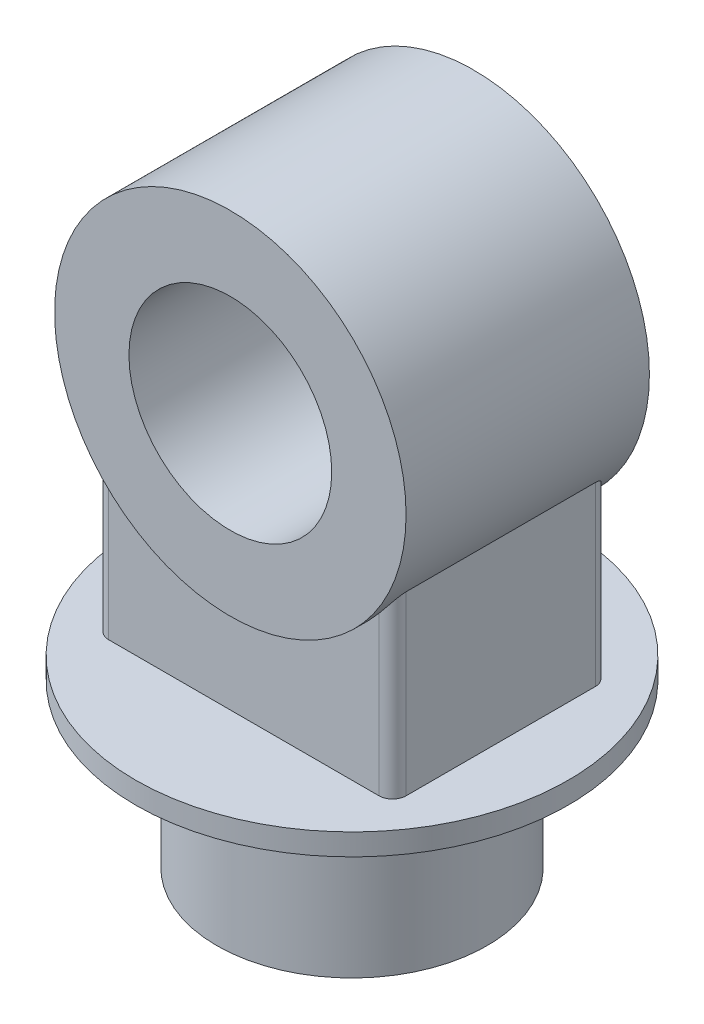
SolidWorks part; units mm, degrees
ref_plane "Front Plane" through (0, 0, 0) normal (0, 0, 1) x (1, 0, 0)
ref_plane "Top Plane" through (0, 0, 0) normal (0, 1, 0) x (1, 0, 0)
ref_plane "Right Plane" through (0, 0, 0) normal (1, 0, 0) x (0, 0, -1)
sketch "Sketch1" plane through (0, 0, 0) normal (0, 1, 0) x (1, 0, 0)
  circle A0 centre (0, 0) radius 2540
  dimension "D1" = 5080
extrude "Boss-Extrude1" add sketch "Sketch1" along normal blind 3048
sketch "Sketch2" plane through (0, 3048, 0) normal (0, 1, 0) x (1, 0, 0)
  circle A0 centre (0, 0) radius 4064
  dimension "D1" = 8128
extrude "Boss-Extrude2" add sketch "Sketch2" along normal blind 406.4
sketch "Sketch3" plane through (0, 0, 0) normal (0, 0, 1) x (1, 0, 0)
  line L0 (4064, 3454.4) -> (-4064, 3454.4) construction
  circle A0 centre (0, 8534.4) radius 3302
  circle A1 centre (0, 8534.4) radius 1905
  dimension "D2" = 6604
  dimension "D3" = 3810
  dimension "D1" = 5080
extrude "Boss-Extrude3" add sketch "Sketch3" along normal mid plane 4572 separate body
sketch "Sketch4" plane through (0, 3454.4, 0) normal (0, 1, 0) x (1, 0, 0)
  line L1 (2794, 2032) -> (-2794, 2032)
  line L2 (2794, 2032) -> (2794, -2032)
  line L3 (2794, -2032) -> (-2794, -2032)
  line L4 (-2794, 2032) -> (-2794, -2032)
  line L5 (2794, 2032) -> (-2794, -2032) construction
  line L6 (2794, -2032) -> (-2794, 2032) construction
  point P0 (0, 0)
  dimension "D1" = 4064
  dimension "D2" = 5588
extrude "Boss-Extrude4" add sketch "Sketch4" along normal up to next
fillet "Fillet1" radius 254 4 edges at (-2794, 5114.5182, -2032) (2794, 5114.5182, -2032) (2794, 5114.5182, 2032) (-2794, 5114.5182, 2032)
